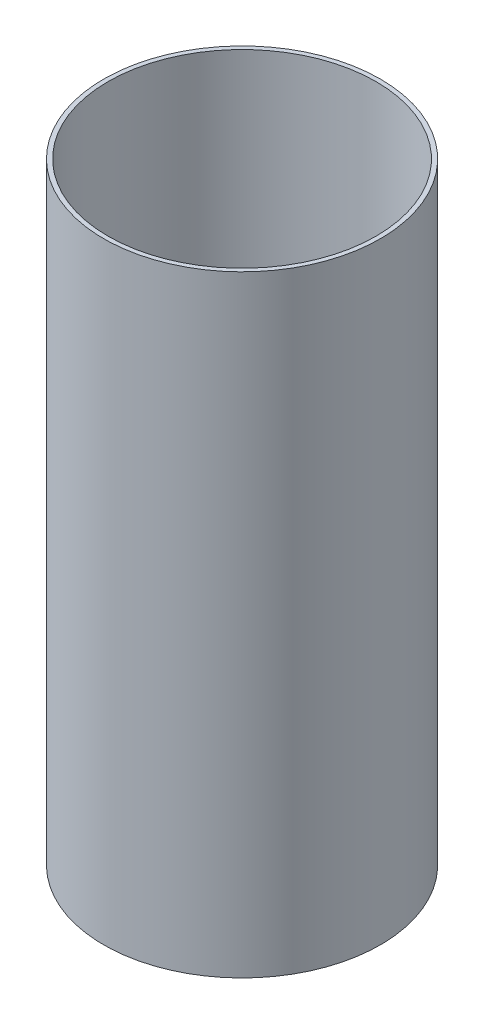
SolidWorks part; units mm, degrees
ref_plane "Front Plane" through (0, 0, 0) normal (0, 0, 1) x (1, 0, 0)
ref_plane "Top Plane" through (0, 0, 0) normal (0, 1, 0) x (1, 0, 0)
ref_plane "Right Plane" through (0, 0, 0) normal (1, 0, 0) x (0, 0, -1)
sketch "Sketch1" plane through (0, 0, 0) normal (0, 1, 0) x (1, 0, 0)
  circle A0 centre (0, 0) radius 18.4
  circle A1 centre (0, 0) radius 19
  dimension "D1" = 38
  dimension "D2" = 0.6
extrude "Boss-Extrude1" add sketch "Sketch1" along normal mid plane 84
